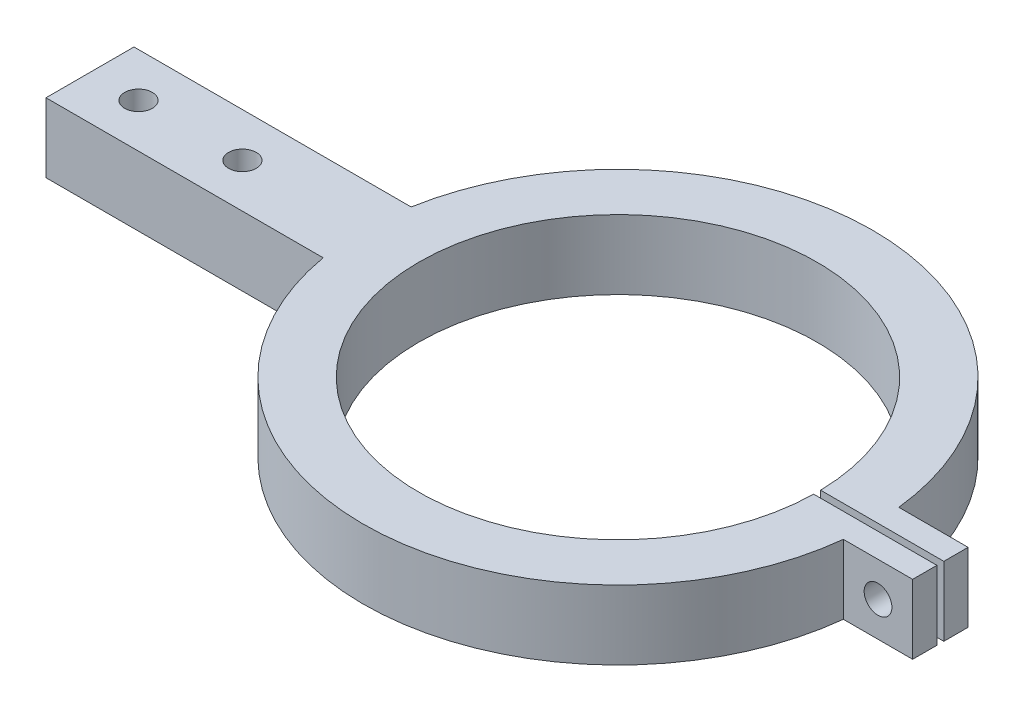
SolidWorks part; units mm, degrees
ref_plane "Front" through (0, 0, 0) normal (0, 0, 1) x (1, 0, 0)
ref_plane "Top" through (0, 0, 0) normal (0, 1, 0) x (1, 0, 0)
ref_plane "Right" through (0, 0, 0) normal (1, 0, 0) x (0, 0, -1)
sketch "Sketch1" plane through (0, 0, 0) normal (0, 1, 0) x (1, 0, 0)
  line L0 (0, 0) -> (-80.7672, 0) construction
  line L1 (0, 0) -> (61.9809, 0) construction
  line L2 (-76.1972, -6.35) -> (-36.1972, -6.35)
  line L3 (-76.1972, -6.35) -> (-76.1972, 6.35)
  line L4 (-76.1972, 6.35) -> (-36.1972, 6.35)
  line L6 (-76.1972, -6.35) -> (-36.1972, 6.35) construction
  line L7 (-76.1972, 6.35) -> (-36.1972, -6.35) construction
  line L8 (46.5317, 0.5) -> (46.5317, 4)
  line L9 (46.5317, -4) -> (36.5317, -4)
  line L10 (46.5317, -4) -> (46.5317, -0.5)
  line L11 (46.5317, 4) -> (36.5317, 4)
  line L13 (46.5317, -4) -> (36.5317, 4) construction
  line L14 (46.5317, 4) -> (36.5317, -4) construction
  line L15 (28.7457, -0.5) -> (46.5317, -0.5)
  line L16 (28.7457, 0.5) -> (46.5317, 0.5)
  arc A0 (28.7457, 0.5) -> (28.7457, -0.5) centre (0, 0) ccw
  arc A1 (36.5317, 4) -> (-36.1972, 6.35) centre (0, 0) ccw
  circle A2 centre (-69.1972, 0) radius 2
  circle A3 centre (-54.1972, 0) radius 2
  arc A4 (-36.1972, -6.35) -> (36.5317, -4) centre (0, 0) ccw
  point P4 (-56.1972, 0)
  point P14 (41.5317, 0)
  point P20 (28.75, 0)
  point P21 (46.5317, 0)
  dimension "D1" = 57.5
  dimension "D2" = 8
  dimension "D5" = 4
  dimension "D6" = 4
  dimension "D3" = 40
  dimension "D4" = 12.7
  dimension "D7" = 15
  dimension "D8" = 7
  dimension "D9" = 8
  dimension "D10" = 10
extrude "Boss-Extrude2" add sketch "Sketch1" along normal blind 10 contours A1 L4 L3 L2 A4 L9 L10 L15 A0 L16 L8 L11 | A2 | A3
sketch "Sketch2" plane through (0, 0, 4) normal (0, 0, 1) x (1, 0, 0)
  line L0 (41.5317, 10) -> (41.5317, 0) construction
  line L1 (46.5317, 10) -> (36.5317, 10) construction
  line L2 (46.5317, 0) -> (36.5317, 0) construction
  circle A0 centre (41.5317, 5) radius 2
  dimension "D1" = 4
extrude "Cut-Extrude1" cut sketch "Sketch2" against normal through all
